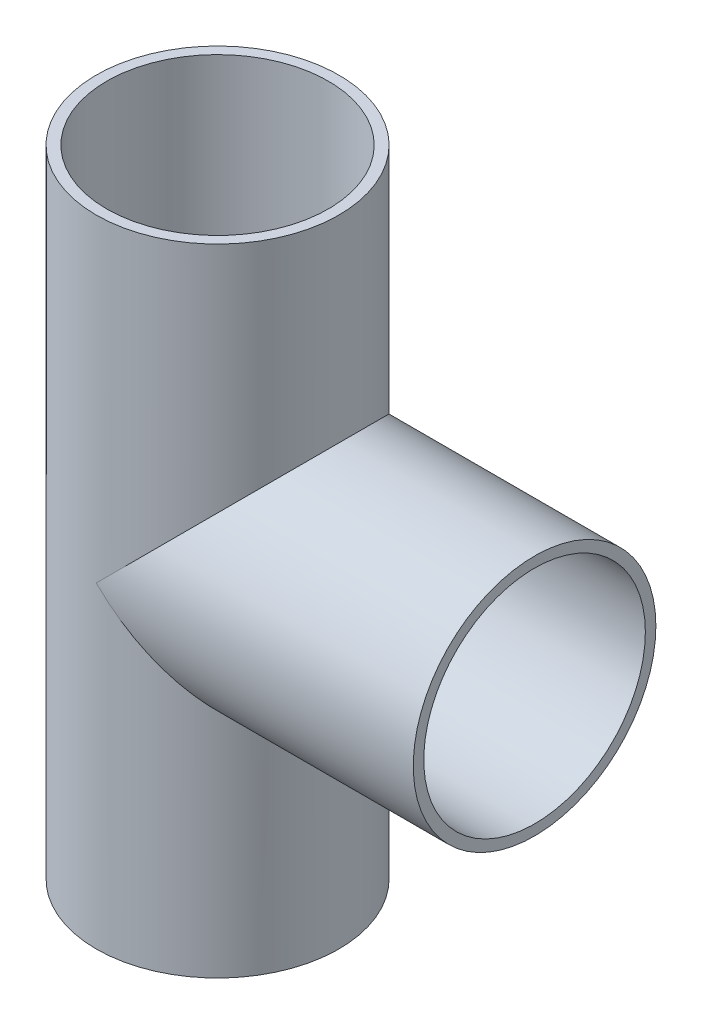
SolidWorks part; units mm, degrees
ref_plane "Front Plane" through (0, 0, 0) normal (0, 0, 1) x (1, 0, 0)
ref_plane "Top Plane" through (0, 0, 0) normal (0, 1, 0) x (1, 0, 0)
ref_plane "Right Plane" through (0, 0, 0) normal (1, 0, 0) x (0, 0, -1)
sketch "Sketch1" plane through (0, 0, 0) normal (0, 1, 0) x (1, 0, 0)
  circle A0 centre (0, 0) radius 19.05
  dimension "D1" = 38.1
extrude "Extrude1" add sketch "Sketch1" along normal blind 50.038 and the other way blind 49.784
sketch "Sketch2" plane through (0, 0, 0) normal (0, 1, 0) x (1, 0, 0)
  line L0 (0, 0) -> (49.784, 0)
  dimension "D1" = 49.784
ref_plane "Plane1" through (49.784, 0, 0) normal (1, 0, 0) x (0, 0, -1)
sketch "Sketch3" plane through (49.784, 0, 0) normal (1, 0, 0) x (0, 0, -1)
  circle A0 centre (0, 0) radius 19.05
extrude "Extrude2" add sketch "Sketch3" against normal up to body separate body
sketch "Sketch4" plane through (49.784, 0, 0) normal (1, 0, 0) x (0, 0, -1)
  circle A0 centre (0, 0) radius 17.399
  dimension "D1" = 34.798
extrude "Cut-Extrude1" cut sketch "Sketch4" against normal up to vertex (49.784 mm away) up to point (0, 0, 0)
sketch "Sketch5" plane through (0, 0, 0) normal (0, 1, 0) x (1, 0, 0)
  circle A0 centre (0, 0) radius 17.399
  dimension "D1" = 34.798
extrude "Cut-Extrude2" cut sketch "Sketch5" against normal through all and the other way through all
